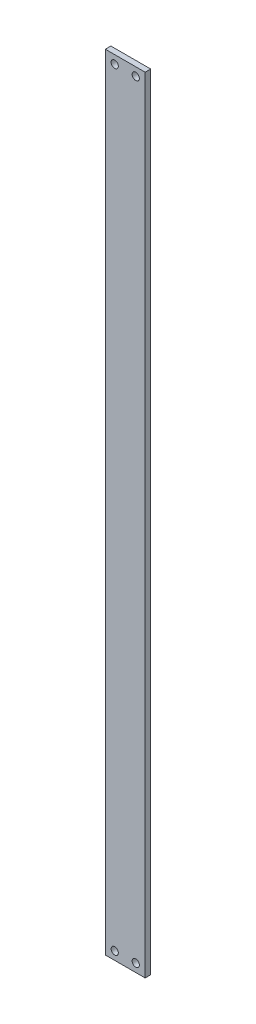
SolidWorks part; units mm, degrees
ref_plane "Piano frontale" through (0, 0, 0) normal (0, 0, 1) x (1, 0, 0)
ref_plane "Piano superiore" through (0, 0, 0) normal (0, 1, 0) x (1, 0, 0)
ref_plane "Piano destro" through (0, 0, 0) normal (1, 0, 0) x (0, 0, -1)
ref_plane "Piano1" through (0, 0, 5) normal (0, 0, 1) x (1, 0, 0)
sketch "Schizzo1" plane through (0, 0, 5) normal (0, 0, 1) x (1, 0, 0)
  line L4 (-2.5, -197.5) -> (-2.5, 511.5)
  line L5 (-2.5, 511.5) -> (-38.5, 511.5)
  line L6 (-38.5, 511.5) -> (-38.5, -197.5)
  line L7 (-38.5, -197.5) -> (-2.5, -197.5)
  circle A0 centre (-30, -190) radius 3.25
  circle A1 centre (-30, 504) radius 3.25
  circle A2 centre (-11, 504) radius 3.25
  circle A3 centre (-11, -190) radius 3.25
  dimension "D1" = 36
  dimension "D2" = 709
  dimension "D3" = 8.5
  dimension "D4" = 8.5
  dimension "D5" = 7.5
  dimension "D6" = 7.5
  dimension "D7" = 8.5
  dimension "D8" = 8.5
  dimension "D9" = 7.5
extrude "Estrusione-Estrusione1" add sketch "Schizzo1" against normal blind 5
